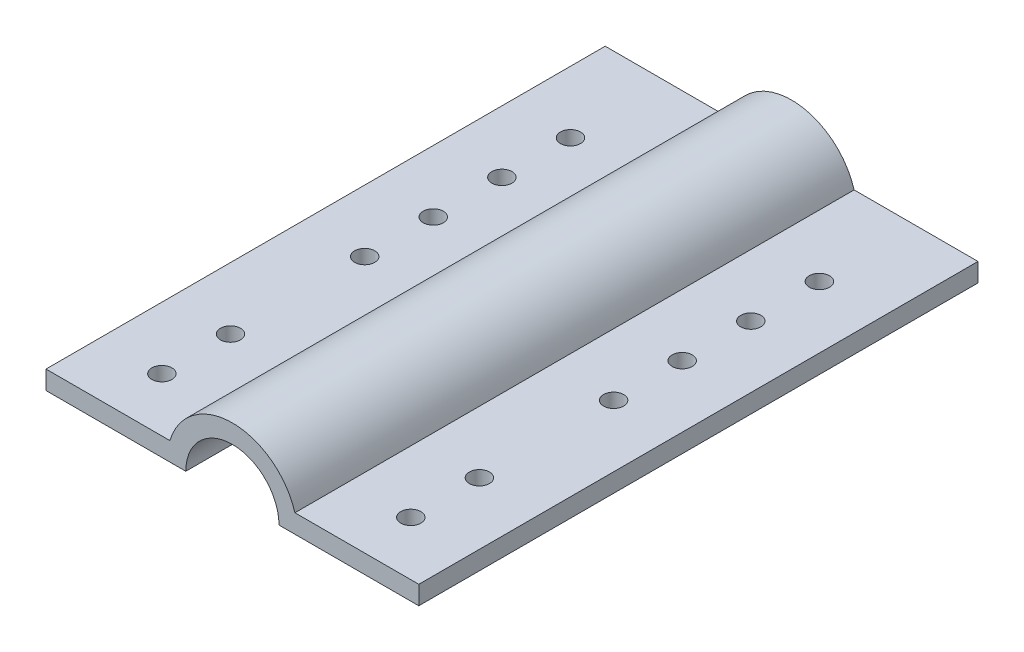
SolidWorks part; units mm, degrees
material "Nylon 6/10"
ref_plane "Front Plane" through (0, 0, 0) normal (0, 0, 1) x (1, 0, 0)
ref_plane "Top Plane" through (0, 0, 0) normal (0, 1, 0) x (1, 0, 0)
ref_plane "Right Plane" through (0, 0, 0) normal (1, 0, 0) x (0, 0, -1)
sketch "Sketch1" plane through (0, 0, 0) normal (0, 0, 1) x (1, 0, 0)
  line L0 (0, 0) -> (-50, 0) construction
  line L1 (-12.5, 0) -> (-50, 0)
  line L2 (0, 0) -> (0, 12.5) construction
  line L3 (12.5, 0) -> (50, 0)
  line L4 (16.7705, 5) -> (50, 5)
  line L5 (-16.7705, 5) -> (-50, 5)
  line L8 (-50, 5) -> (-50, 0)
  line L13 (50, 5) -> (50, 0)
  arc A0 (-12.5, 0) -> (12.5, 0) centre (0, 0) cw
  arc A1 (-16.7705, 5) -> (16.7705, 5) centre (0, 0) cw
  dimension "D1" = 50
  dimension "D3" = 12.5
  dimension "D2" = 5
extrude "Boss-Extrude1" add sketch "Sketch1" along normal blind 100 and the other way blind 50 contours A0 L3 L13 L4 A1 L5 L8 L1
sketch "Sketch2" plane through (0, 5, 0) normal (0, 1, 0) x (1, 0, 0)
  line L0 (0, 0) -> (0, -100.0875) construction
  line L7 (0, -50.0438) -> (-16.7705, -25) construction
  line L8 (-16.7705, -100) -> (-16.7705, 50) construction
  circle A16 centre (0, -50.0438) radius 30 construction
  point P16 (-40, -18)
  point P29 (40, -18)
sketch "Sketch3" plane through (0, 0, 0) normal (0, -1, 0) x (1, 0, 0)
  line L0 (0, 0) -> (0, 100.0875) construction
  line L1 (-12.5, 100) -> (-12.5, -50) construction
  line L2 (-12.5, 71.3522) -> (-12.5, 28.7354)
  line L3 (0, 50.0438) -> (0, 75.0438) construction
  line L4 (12.5, 71.3522) -> (12.5, 28.7354)
  circle A0 centre (0, 50.0438) radius 25 construction
  arc A1 (-12.5, 71.3522) -> (-12.5, 28.7354) centre (0, 50.0438) ccw
  arc A2 (12.5, 71.3522) -> (12.5, 28.7354) centre (0, 50.0438) cw
ref_plane "Plane1" through (-12.5, 0, 0) normal (-1, 0, 0) x (0, 0, 1)
sketch "Sketch4" plane through (-12.5, 0, 0) normal (-1, 0, 0) x (0, 0, 1)
  line L0 (50.0438, 0) -> (50.0438, -12.5) construction
  line L1 (50.0438, 0) -> (48.0549, -13.6331)
sweep "Sweep1" add profiles "Sketch3" path "Sketch4"
sketch "Sketch5" plane through (0, 0, 0) normal (0, -1, 0) x (1, 0, 0)
  line L0 (-12.5, 100) -> (-50, 100) construction
  line L1 (-31.25, 100) -> (-31.25, -50) construction
  line L2 (-12.5, -50) -> (-50, -50) construction
  line L3 (0, 0) -> (0, 102.1791) construction
sketch "Sketch6" plane through (0, 5, 0) normal (0, 1, 0) x (1, 0, 0)
  line L0 (16.7705, -100) -> (50, -100)
  line L1 (33.3853, -100) -> (33.3853, 50) construction
  line L2 (16.7705, 50) -> (50, 50) construction
  line L3 (0, 0) -> (0, -74.9789) construction
  circle A0 centre (33.3853, -85.53) radius 2.7
  circle A1 centre (33.3853, -67.13) radius 2.7
  circle A2 centre (33.3853, 24.07) radius 2.7
  circle A3 centre (33.3853, 5.67) radius 2.7
  circle A4 centre (33.3853, -12.73) radius 2.7
  circle A5 centre (33.3853, -31.13) radius 2.7
  circle A6 centre (-33.3853, -31.13) radius 2.7
  circle A7 centre (-33.3853, -12.73) radius 2.7
  circle A8 centre (-33.3853, 5.67) radius 2.7
  circle A9 centre (-33.3853, 24.07) radius 2.7
  circle A10 centre (-33.3853, -67.13) radius 2.7
  circle A11 centre (-33.3853, -85.53) radius 2.7
  dimension "D1" = 14.47
  dimension "D3" = 25.93
  dimension "D2" = 18.4
  dimension "D4" = 18.4
  dimension "D5" = 18.4
  dimension "D6" = 18.4
extrude "Cut-Extrude2" cut sketch "Sketch6" against normal up to next contours A9 | A8 | A7 | A6 | A10 | A11 | A2 | A3 | A5 | A1 | A0 | A4
